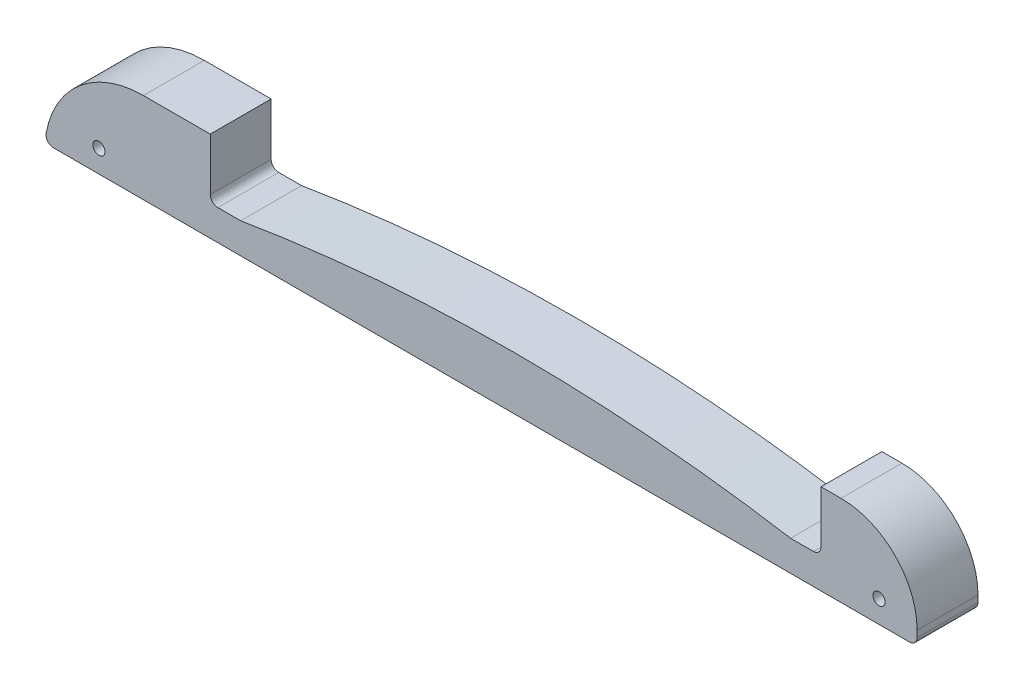
SolidWorks part; units mm, degrees
material "3.1355 (EN-AW 2024)"
ref_plane "Спереди" through (0, 0, 0) normal (0, 0, 1) x (1, 0, 0)
ref_plane "Сверху" through (0, 0, 0) normal (0, 1, 0) x (1, 0, 0)
ref_plane "Справа" through (0, 0, 0) normal (1, 0, 0) x (0, 0, -1)
sketch "Model" plane through (0, 0, 0) normal (0, 0, 1) x (1, 0, 0)
  line L1 (-32.875, 4) -> (-32.875, 11.86)
  line L6 (60, 11.86) -> (47.375, 11.86)
  line L11 (60, 11.86) -> (60, 0)
  line L12 (-41.6501, 11.86) -> (-32.875, 11.86)
  line L17 (47.375, 11.86) -> (47.375, 4)
  line L18 (-47.5, 2.93) -> (0, 2.93) construction
  line L19 (0, 2.93) -> (55, 2.93) construction
  line L20 (-54.6, 0) -> (0, 0)
  line L21 (0, 0) -> (60, 0)
  line L23 (-32.875, 4) -> (-28.875, 4)
  line L24 (47.375, 4) -> (43.375, 4)
  arc A9 (-41.6501, 11.86) -> (-54.6, 0) centre (-41.6501, -1.14) ccw
  circle A20 centre (-47.5, 2.93) radius 0.5
  circle A22 centre (55, 2.93) radius 0.5
  arc A24 (-28.875, 4) -> (43.375, 4) centre (7.25, -213.0138) cw
  point P0 (-31.65, 2.93)
  point P2 (50.15, 11.86)
  point P3 (0, 0)
  point P6 (0, 0)
  point P7 (50.15, 12.4511)
  point P8 (-35.65, 11.8609)
  point P11 (0, 0)
  point P13 (0, 0)
  point P14 (-35.4009, 11.86)
  dimension "D4" = 13
  dimension "D8" = 1
  dimension "D12" = 220
  dimension "D16" = 54.6
  dimension "D2" = 11.86
  dimension "D3" = 80.25
  dimension "D5" = 4
  dimension "D7" = 2.93
  dimension "D11" = 60
  dimension "D13" = 4
  dimension "D14" = 47.5
  dimension "D15" = 55
  dimension "D17" = 7.25
extrude "База" add sketch "Model" against normal blind 8
fillet "Скругление1" radius 10 1 edges at (60, 11.86, -4)
fillet "Скругление2" radius 1 4 edges at (47.375, 4, -4) (-32.875, 4, -4) (-54.6, 0, -4) (60, 0, -4)
hole_wizard "Крепление M2" positions "Эскиз3" profile "Эскиз4" tap size "M2" standard "DIN" end condition through all
sketch "Эскиз3" plane through (0, 0, 0) normal (0, 0, 1) x (1, 0, 0)
  point P0 (-47.5, 2.93)
  point P3 (55, 2.93)
sketch "Эскиз4" plane through (-47.5, 2.93, 0) normal (1, 0, 0) x (0, -1, 0)
  line L0 (0, 0) -> (0, 8)
  line L1 (0, 8) -> (0.8, 8)
  line L2 (0.8, 8) -> (0.8, 0)
  line L5 (0.8, 0) -> (0, 0)
  line L11 (0, -6.35) -> (0, 107.95) construction
  dimension "Диаметр проходного сверла" = 1.6
  dimension "Глубина проходного сверла" = 8
cosmetic thread "Отверстие резьбы1" parameters "D1"=8, "D2"=2
cosmetic thread "Отверстие резьбы2" parameters "D1"=8, "D2"=2
